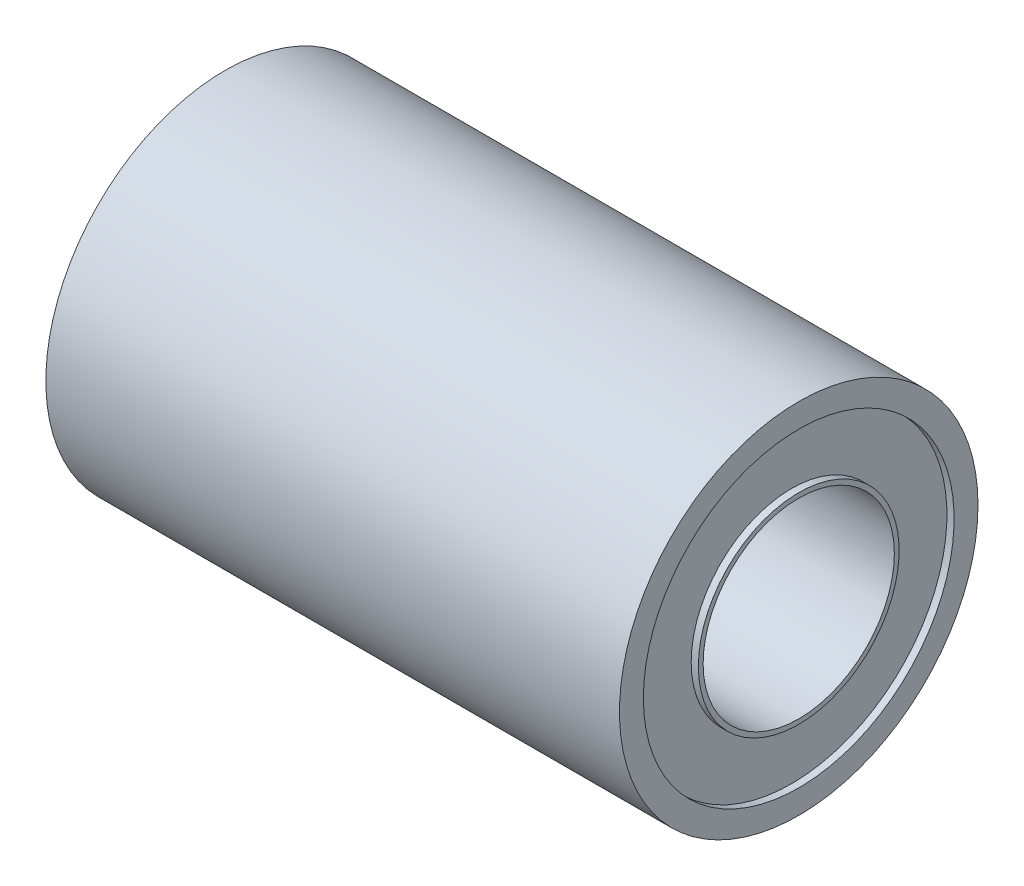
SolidWorks part; units mm, degrees
material "Plain Carbon Steel"
ref_plane "Front Plane" through (0, 0, 0) normal (0, 0, 1) x (1, 0, 0)
ref_plane "Top Plane" through (0, 0, 0) normal (0, 1, 0) x (1, 0, 0)
ref_plane "Right Plane" through (0, 0, 0) normal (1, 0, 0) x (0, 0, -1)
sketch "Sketch1" plane through (0, 0, 0) normal (1, 0, 0) x (0, 0, -1)
  circle A0 centre (0, 0) radius 7.5
  circle A1 centre (0, 0) radius 4
  dimension "D1" = 8
  dimension "D2" = 15
extrude "Boss-Extrude1" add sketch "Sketch1" along normal blind 24
sketch "Sketch2" plane through (0, 0, 0) normal (0, 0, 1) x (1, 0, 0)
  line L0 (24, 6.5) -> (23.7, 6.5)
  line L1 (24, -7.5) -> (24, 7.5) construction
  line L2 (23.7, 6.5) -> (23.7, 4.2)
  line L3 (23.7, 4.2) -> (24, 4.2)
  line L4 (24, 4.2) -> (24, 6.5)
  line L5 (0, 0) -> (24, 0) construction
  line L6 (0, 7.5) -> (0, -7.5) construction
  line L7 (24, 7.5) -> (0, 7.5) construction
  line L8 (24, 4.2) -> (24, 4) construction
  line L11 (12, 0) -> (12, 4.7704) construction
  line L12 (0, 4.2) -> (0, 4) construction
  line L13 (0, 4.2) -> (0, 6.5)
  line L14 (0.3, 4.2) -> (0, 4.2)
  line L15 (0.3, 6.5) -> (0.3, 4.2)
  line L16 (0, 6.5) -> (0.3, 6.5)
  dimension "D1" = 1
  dimension "D2" = 0.2
  dimension "D3" = 0.3
revolve "Cut-Revolve1" cut sketch "Sketch2" angle 360 about L5
